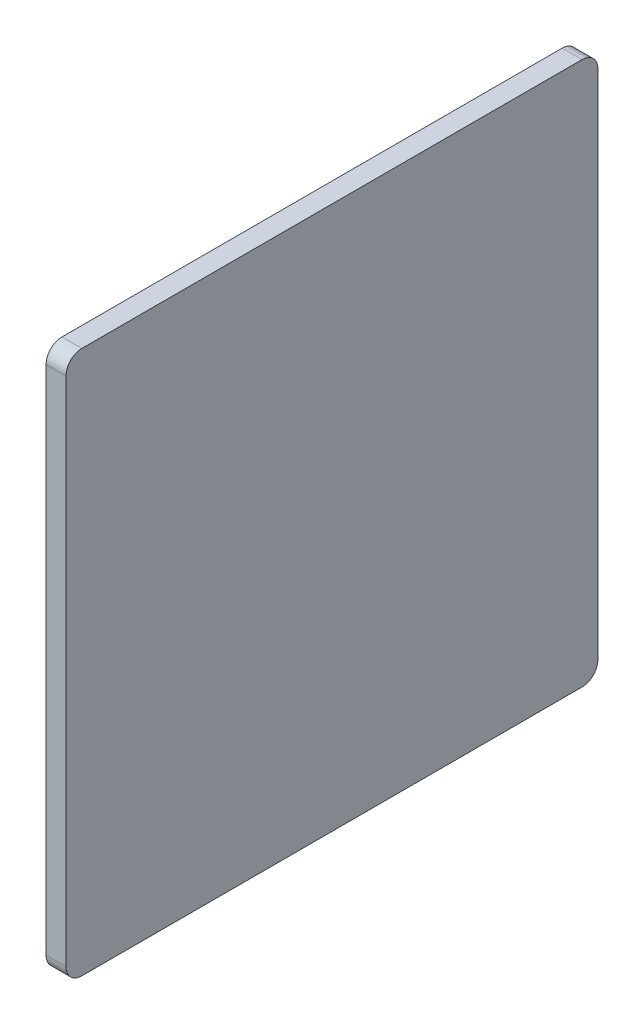
SolidWorks part; units mm, degrees
material "Acrylic (Medium-high impact)"
ref_plane "Front Plane" through (0, 0, 0) normal (0, 0, 1) x (1, 0, 0)
ref_plane "Top Plane" through (0, 0, 0) normal (0, 1, 0) x (1, 0, 0)
ref_plane "Right Plane" through (0, 0, 0) normal (1, 0, 0) x (0, 0, -1)
sketch "Sketch1" plane through (0, 0, 0) normal (1, 0, 0) x (0, 0, -1)
  line L1 (42.5, -43.4125) -> (-42.5, -43.4125)
  line L2 (42.5, -43.4125) -> (42.5, 43.4125)
  line L3 (42.5, 43.4125) -> (-42.5, 43.4125)
  line L4 (-42.5, -43.4125) -> (-42.5, 43.4125)
  line L5 (42.5, -43.4125) -> (-42.5, 43.4125) construction
  line L6 (42.5, 43.4125) -> (-42.5, -43.4125) construction
  point P0 (0, 0)
  dimension "D1" = 85
  dimension "D2" = 86.825
extrude "Boss-Extrude1" add sketch "Sketch1" along normal blind 3.175
fillet "Fillet1" radius 2.54 4 edges at (1.5875, -43.4125, 42.5) (1.5875, -43.4125, -42.5) (1.5875, 43.4125, -42.5) (1.5875, 43.4125, 42.5)
